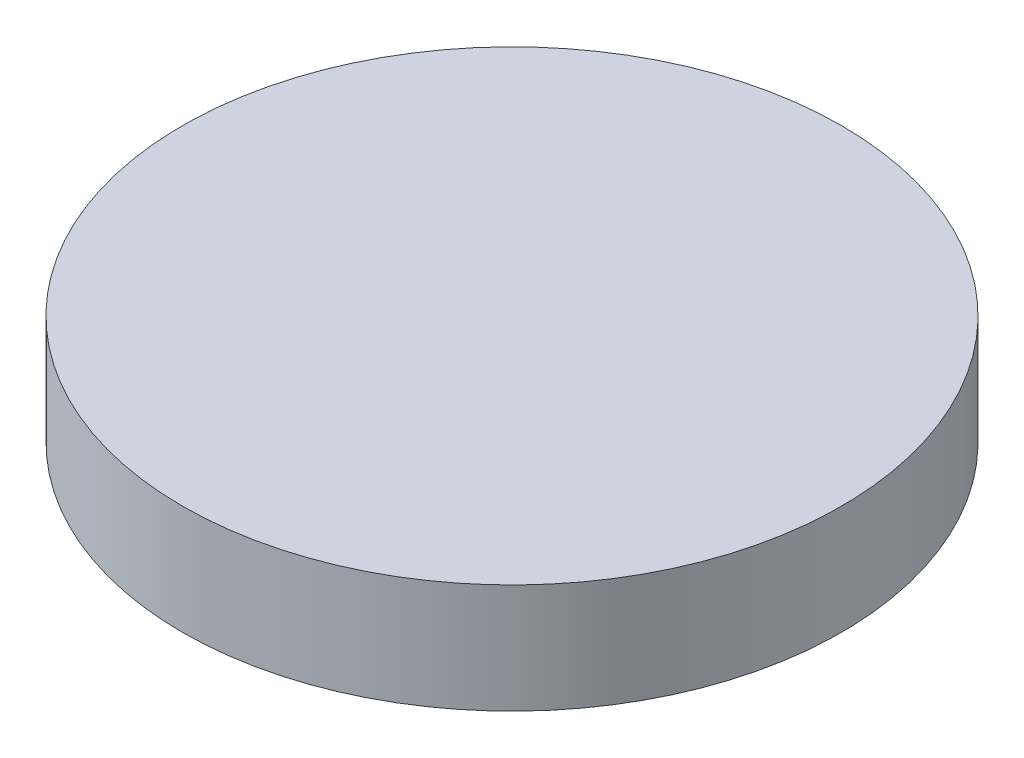
SolidWorks part; units mm, degrees
other "标注1"
sketch "草图3" plane through (-22.25, 4, -10) normal (-0.231, 0.6469, -0.7268) x (-0.9696, -0.2151, 0.1167)
ref_plane "前视基准面" through (0, 0, 0) normal (0, 0, 1) x (1, 0, 0)
ref_plane "上视基准面" through (0, 0, 0) normal (0, 1, 0) x (1, 0, 0)
ref_plane "右视基准面" through (0, 0, 0) normal (1, 0, 0) x (0, 0, -1)
other "Configuration Table"
sketch "草图4" plane through (0, 0, 0) normal (0, 1, 0) x (1, 0, 0)
  circle A1 centre (0, 0) radius 4.975
  dimension "D2" = 9.95
extrude "凸台-拉伸1" add sketch "草图4" along normal blind 1.65
